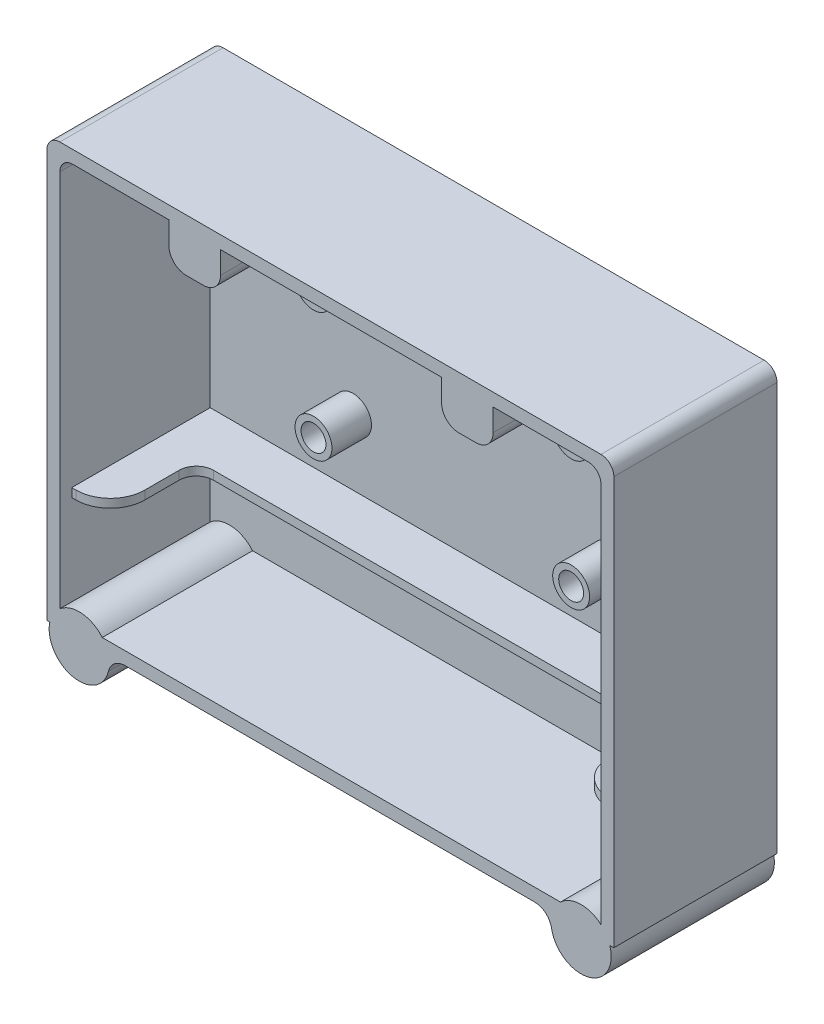
SolidWorks part; units mm, degrees
ref_plane "Front Plane" through (0, 0, 0) normal (0, 0, 1) x (1, 0, 0)
ref_plane "Top Plane" through (0, 0, 0) normal (0, 1, 0) x (1, 0, 0)
ref_plane "Right Plane" through (0, 0, 0) normal (1, 0, 0) x (0, 0, -1)
other "Graphic1"
other "object_1 (Open) -1"
ref_plane "Plane1" through (0, 0, 30) normal (0, 0, 1) x (1, 0, 0)
sketch "Sketch1" plane through (0, 0, 30) normal (0, 0, 1) x (1, 0, 0)
  line L1 (72.8096, 320.0447) -> (138.8096, 320.0447)
  line L2 (72.8096, 320.0447) -> (72.8096, 271.0447)
  line L3 (72.8096, 271.0447) -> (138.8096, 271.0447)
  line L4 (138.8096, 320.0447) -> (138.8096, 271.0447)
  dimension "D1" = 66
  dimension "D2" = 49
extrude "Boss-Extrude1" add sketch "Sketch1" along normal blind 19
shell "Shell1" thickness 1.5
sketch "Sketch2" plane through (0, 0, 31.5) normal (0, 0, 1) x (1, 0, 0)
  line L0 (137.3096, 318.5447) -> (74.3096, 318.5447) construction
  line L1 (87.0113, 318.5447) -> (93.0113, 318.5447)
  line L3 (87.0113, 313.9447) -> (93.0113, 313.9447)
  line L4 (93.0113, 318.5447) -> (93.0113, 313.9447)
  line L5 (87.0113, 318.5447) -> (87.0113, 313.9447)
  line L6 (118.7567, 318.5447) -> (124.7567, 318.5447)
  line L7 (118.7567, 318.5447) -> (118.7567, 313.9447)
  line L8 (118.7567, 313.9447) -> (124.7567, 313.9447)
  line L9 (124.7567, 318.5447) -> (124.7567, 313.9447)
  dimension "D1" = 6
  dimension "D2" = 4.6
extrude "Boss-Extrude2" add sketch "Sketch2" along normal up to surface (17.5 mm away) up to face at (105.8096, 295.5447, 49)
fillet "Fillet1" radius 1.5 4 edges at (137.3096, 318.5447, 40.25) (74.3096, 318.5447, 40.25) (72.8096, 320.0447, 39.5) (138.8096, 320.0447, 39.5)
sketch "Sketch3" plane through (0, 0, 31.5) normal (0, 0, 1) x (1, 0, 0)
  circle A0 centre (90.9398, 307.1114) radius 1.45
  circle A1 centre (90.9398, 307.1114) radius 2.15
  circle A5 centre (120.9398, 307.1114) radius 2.15
  circle A6 centre (120.9398, 307.1114) radius 1.45
  circle A7 centre (120.9398, 292.1114) radius 2.15
  circle A8 centre (120.9398, 292.1114) radius 1.45
  circle A9 centre (90.9398, 292.1114) radius 2.15
  circle A10 centre (90.9398, 292.1114) radius 1.45
  dimension "D1" = 2
  dimension "D2" = 2
extrude "Boss-Extrude3" add sketch "Sketch3" along normal blind 4.6
ref_plane "Plane2" through (0, 284, 0) normal (0, 1, 0) x (1, 0, 0)
sketch "Sketch4" plane through (0, 284, 0) normal (0, 1, 0) x (1, 0, 0)
  line L0 (72.8096, -47.6156) -> (78.8096, -47.6156)
  line L1 (72.8096, -49) -> (72.8096, -30) construction
  line L2 (78.8096, -47.6156) -> (78.8096, -37.6156)
  line L3 (78.8096, -37.6156) -> (132.8096, -37.6156)
  line L4 (132.8096, -37.6156) -> (132.8096, -47.6156)
  line L5 (132.8096, -47.6156) -> (138.8096, -47.6156)
  line L6 (138.8096, -49) -> (138.8096, -30) construction
  line L7 (138.8096, -47.6156) -> (138.8096, -30)
  line L8 (-39.0934, -30) -> (39.0934, -30) construction
  line L9 (138.8096, -30) -> (72.8096, -30)
  line L10 (72.8096, -30) -> (72.8096, -47.6156)
  dimension "D1" = 6
extrude "Boss-Extrude4" add sketch "Sketch4" along normal mid plane 1
fillet "Fillet2" radius 4 2 edges at (78.8096, 284, 47.6156) (132.8096, 284, 47.6156)
fillet "Fillet3" radius 2 2 edges at (132.8096, 284, 37.6156) (78.8096, 284, 37.6156)
sketch "Sketch5" plane through (0, 0, 49) normal (0, 0, 1) x (1, 0, 0)
  circle A0 centre (76.561, 270.2994) radius 3.5
  circle A1 centre (135, 270) radius 3.5
  dimension "D1" = 7
extrude "Boss-Extrude5" add sketch "Sketch5" against normal up to surface (19 mm away) up to face at (105.8096, 303.3149, 30)
fillet "Fillet4" radius 2 6 edges at (131.6595, 271.0447, 39.5) (79.9808, 271.0447, 39.5) (124.7567, 313.9447, 40.25) (118.7567, 313.9447, 40.25) (87.0113, 313.9447, 40.25) (93.0113, 313.9447, 40.25)
